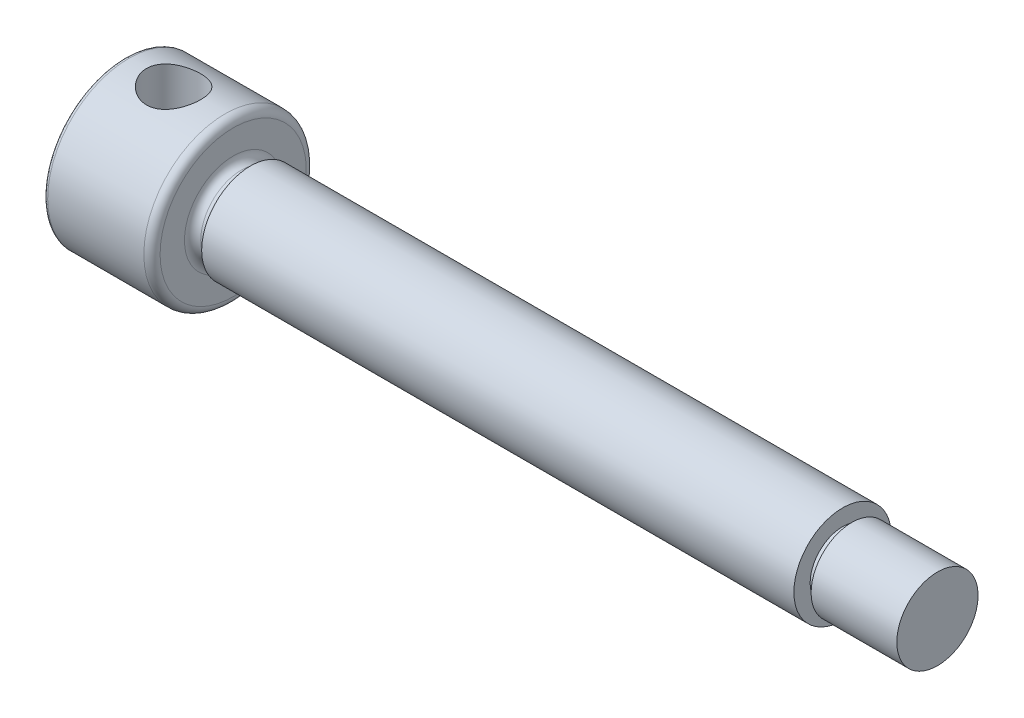
SolidWorks part; units mm, degrees
ref_plane "Front Plane" through (0, 0, 0) normal (0, 0, 1) x (1, 0, 0)
ref_plane "Top Plane" through (0, 0, 0) normal (0, 1, 0) x (1, 0, 0)
ref_plane "Right Plane" through (0, 0, 0) normal (1, 0, 0) x (0, 0, -1)
sketch "Sketch1" plane through (0, 0, 0) normal (0, 0, 1) x (1, 0, 0)
  line L0 (0, 0) -> (23817.8268, 0) construction
  line L1 (0, 0) -> (0, 30)
  line L2 (0, 30) -> (40, 30)
  line L3 (40, 30) -> (40, 15)
  line L4 (40, 15) -> (46.35, 15)
  line L5 (46.35, 15) -> (46.35, 18)
  line L6 (46.35, 18) -> (265, 18)
  line L7 (265, 18) -> (265, 12)
  line L8 (265, 12) -> (268.35, 12)
  line L9 (268.35, 15) -> (300, 15)
  line L10 (300, 15) -> (300, 0)
  line L11 (268.35, 15) -> (268.35, 12)
  line L12 (0, 0) -> (300, 0)
  dimension "D1" = 30
  dimension "D2" = 40
  dimension "D3" = 15
  dimension "D4" = 3
  dimension "D5" = 6.35
  dimension "D6" = 15
  dimension "D7" = 6
  dimension "D8" = 3.35
  dimension "D9" = 300
  dimension "D10" = 35
revolve "Revolve1" add sketch "Sketch1" angle 360 about L0
cosmetic thread "Cosmetic Thread1" parameters "D2"=35
fillet "Fillet1" radius 1.5 1 edges at (0, 0, 30)
sketch "Sketch2" plane through (0, 0, 0) normal (0, 1, 0) x (1, 0, 0)
  line L0 (0, 0) -> (36, 0) construction
  circle A0 centre (18, 0) radius 10
  dimension "D1" = 20
  dimension "D2" = 18
extrude "Cut-Extrude1" cut sketch "Sketch2" against normal through all both and the other way through all
fillet "Fillet2" radius 3 2 edges at (40, 0, 15) (40, 0, 30)
